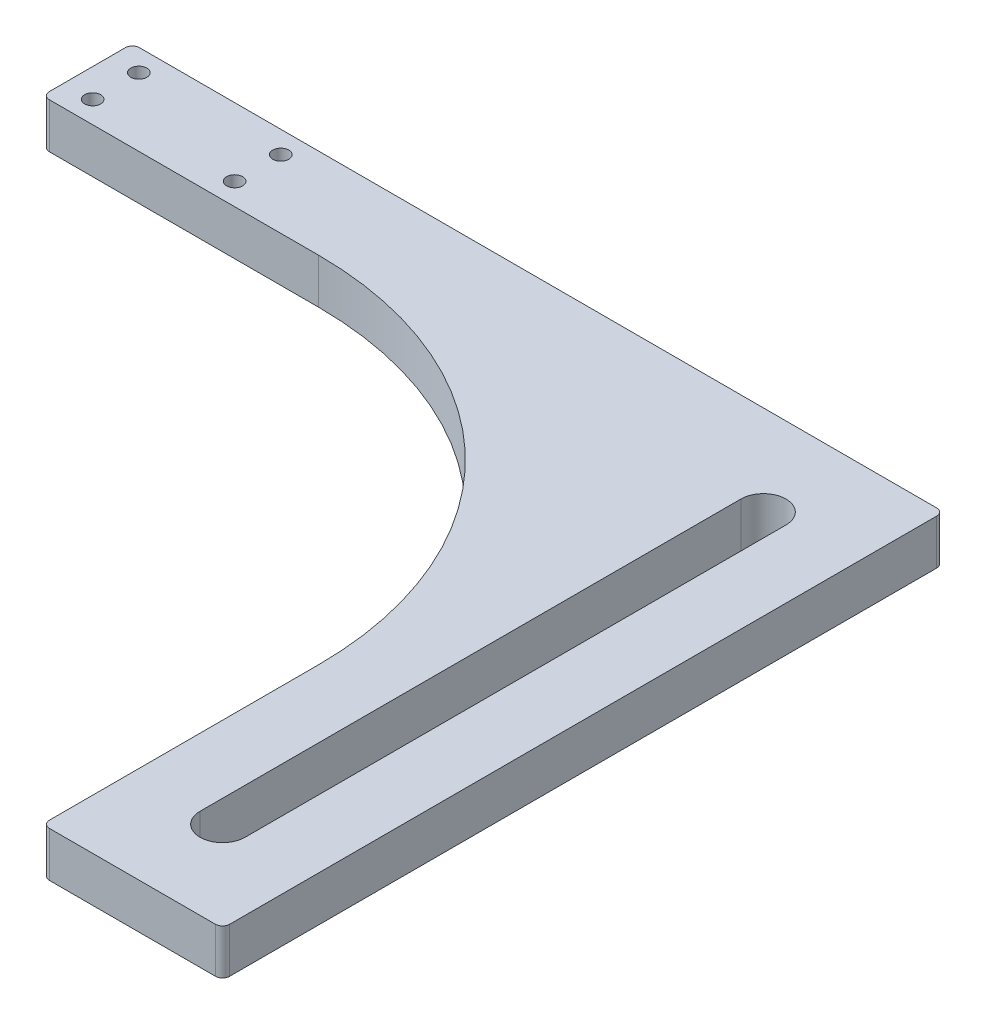
SolidWorks part; units mm, degrees
ref_plane "Front Plane" through (0, 0, 0) normal (0, 0, 1) x (1, 0, 0)
ref_plane "Top Plane" through (0, 0, 0) normal (0, 1, 0) x (1, 0, 0)
ref_plane "Right Plane" through (0, 0, 0) normal (1, 0, 0) x (0, 0, -1)
sketch "Sketch1" plane through (0, 0, 0) normal (0, 1, 0) x (1, 0, 0)
  line L0 (-12.7, 50.8) -> (-101.6, 50.8)
  line L1 (-12.7, -50.8) -> (12.7, -50.8)
  line L2 (-12.7, -50.8) -> (-12.7, 50.8) construction
  line L3 (-12.7, 50.8) -> (12.7, 50.8)
  line L4 (12.7, -50.8) -> (12.7, 50.8)
  line L5 (-12.7, -50.8) -> (12.7, 50.8) construction
  line L6 (-12.7, 50.8) -> (12.7, -50.8) construction
  line L7 (-101.6, 50.8) -> (-101.6, 38.1)
  line L8 (-101.6, 38.1) -> (-62.7, 38.1)
  line L9 (-12.7, -11.9) -> (-12.7, -50.8)
  line L10 (0, -38.1) -> (0, 38.1) construction
  line L13 (-3.175, -38.1) -> (-3.175, 38.1)
  line L14 (3.175, -38.1) -> (3.175, 38.1)
  line L15 (-97.6, 50.8) -> (-97.6, 38.1) construction
  line L16 (-77.6, 50.8) -> (-77.6, 38.1) construction
  line L17 (-97.6, 47.7) -> (-97.6, 50.8) construction
  line L18 (-97.6, 41.2) -> (-97.6, 38.1) construction
  line L19 (-97.6, 47.7) -> (-77.6, 47.7) construction
  line L20 (-97.6, 41.2) -> (-77.6, 41.2) construction
  arc A2 (-62.7, 38.1) -> (-12.7, -11.9) centre (-62.7, -11.9) cw
  arc A3 (-3.175, -38.1) -> (3.175, -38.1) centre (0, -38.1) ccw
  arc A4 (3.175, 38.1) -> (-3.175, 38.1) centre (0, 38.1) ccw
  circle A5 centre (-97.6, 47.7) radius 1.1303
  circle A6 centre (-97.6, 41.2) radius 1.1303
  circle A7 centre (-77.6, 47.7) radius 1.1303
  circle A8 centre (-77.6, 41.2) radius 1.1303
  point P0 (0, 0)
  point P11 (0, 0)
  point P18 (-12.7, 38.1)
  dimension "D7" = 50
  dimension "D11" = 2.2606
  dimension "D1" = 25.4
  dimension "D2" = 101.6
  dimension "D3" = 101.6
  dimension "D4" = 12.7
  dimension "D5" = 6.35
  dimension "D6" = 12.7
  dimension "D8" = 76.2
  dimension "D9" = 4
  dimension "D10" = 20
  dimension "D12" = 6.5
extrude "Boss-Extrude2" add sketch "Sketch1" along normal blind 6.35
fillet "Fillet1" radius 1 5 edges at (-12.7, 3.175, 50.8) (12.7, 3.175, 50.8) (12.7, 3.175, -50.8) (-101.6, 3.175, -50.8) (-101.6, 3.175, -38.1)
